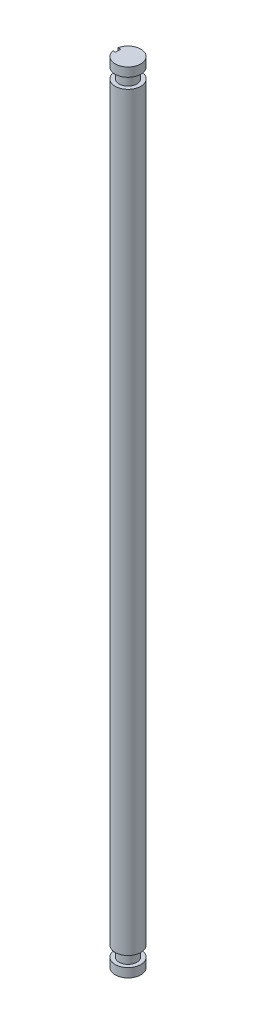
SolidWorks part; units mm, degrees
ref_plane "Front Plane" through (0, 0, 0) normal (1, 0, 0) x (0, 1, 0)
ref_plane "Top Plane" through (0, 0, 0) normal (0, 0, 1) x (0, 1, 0)
ref_plane "Right Plane" through (0, 0, 0) normal (0, 1, 0) x (-1, 0, 0)
sketch "Sketch1" plane through (0, 0, 0) normal (0, 0, 1) x (0, 1, 0)
  line L0 (-976.376, 0) -> (-976.376, 31.7309)
  line L1 (-976.376, 31.7309) -> (-954.024, 31.7309)
  line L2 (-954.024, 31.7309) -> (-954.024, 22.0218)
  line L3 (-954.024, 22.0218) -> (-928.2176, 22.0218)
  line L4 (-928.2176, 22.0218) -> (-928.2176, 31.7309)
  line L5 (-928.2176, 31.7309) -> (928.3446, 31.7309)
  line L6 (928.3446, 31.7309) -> (928.3446, 22.0218)
  line L7 (928.3446, 22.0218) -> (954.151, 22.0218)
  line L8 (954.151, 22.0218) -> (954.151, 31.7309)
  line L9 (954.151, 31.7309) -> (976.376, 31.7309)
  line L10 (976.376, 31.7309) -> (976.376, 0)
  line L11 (976.376, 0) -> (-976.376, 0)
  line L12 (-1001.776, 0) -> (1001.776, 0) construction
revolve "Revolve1" add sketch "Sketch1" angle 360 about L12
sketch "Sketch2" plane through (0, 0, 0) normal (0, 1, 0) x (-1, 0, 0)
  line L1 (24.6062, -6.35) -> (88.0682, -6.35)
  line L2 (24.6062, -6.35) -> (24.6062, 6.35)
  line L3 (24.6062, 6.35) -> (88.0682, 6.35)
  line L4 (88.0682, -6.35) -> (88.0682, 6.35)
extrude "Cut-Extrude2" cut sketch "Sketch2" along normal blind 1997.456 from offset 998.728
